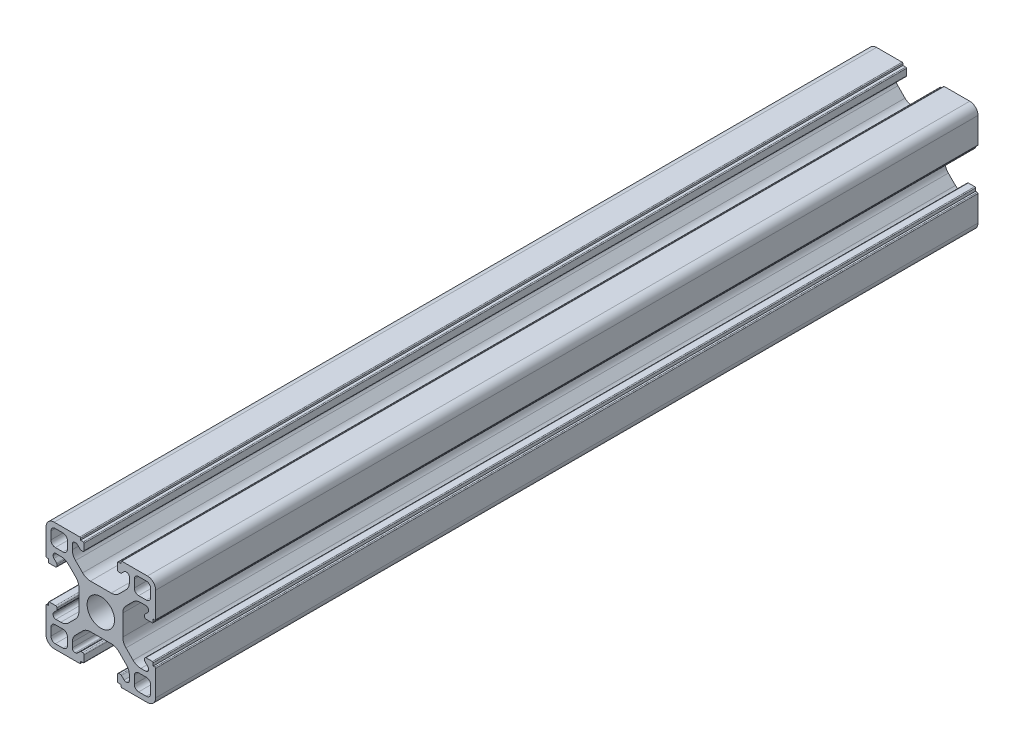
SolidWorks part; units mm, degrees
material "1060 Сплав"
ref_plane "Спереди" through (0, 0, 0) normal (0, 0, 1) x (1, 0, 0)
ref_plane "Сверху" through (0, 0, 0) normal (0, 1, 0) x (1, 0, 0)
ref_plane "Справа" through (0, 0, 0) normal (1, 0, 0) x (0, 0, -1)
sketch "Эскиз1" plane through (0, 0, 0) normal (0, 0, 1) x (1, 0, 0)
  line L0 (-22.0052, 70.3096) -> (-25.0052, 67.3096) construction
  line L1 (-31.1052, 65.2096) -> (-29.2064, 65.2096)
  line L2 (-31.1052, 61.2096) -> (-21.1052, 71.2096) construction
  line L3 (-23.5052, 68.8096) -> (-25.0052, 70.3096) construction
  line L4 (-27.7922, 65.7954) -> (-26.4909, 67.0967)
  line L5 (-24.2052, 67.3096) -> (-22.8052, 67.3096)
  line L6 (-25.0052, 68.1096) -> (-25.0052, 69.5096)
  line L7 (-22.8052, 70.3096) -> (-24.2052, 70.3096)
  line L8 (-25.9052, 69.4096) -> (-25.9052, 68.5109)
  line L9 (-27.3419, 69.2829) -> (-26.8616, 69.7632)
  line L10 (-27.9052, 70.7587) -> (-27.4052, 70.7587)
  line L11 (-27.5187, 69.2096) -> (-27.8052, 69.2096)
  line L12 (-26.508, 69.9096) -> (-26.4052, 69.9096)
  line L13 (-27.4052, 71.0596) -> (-27.4052, 70.7587)
  line L14 (-28.0552, 70.6087) -> (-28.0552, 69.4596)
  line L15 (-22.6052, 71.2096) -> (-27.2552, 71.2096)
  line L16 (-22.0052, 69.5096) -> (-22.0052, 68.1096)
  line L17 (-21.1052, 69.7096) -> (-21.1052, 65.0596)
  line L18 (-21.7061, 64.2596) -> (-22.8552, 64.2596)
  line L19 (-21.2552, 64.9096) -> (-21.5561, 64.9096)
  line L20 (-22.4052, 65.8068) -> (-22.4052, 65.9096)
  line L21 (-23.1052, 64.7961) -> (-23.1052, 64.5096)
  line L22 (-21.5561, 64.4096) -> (-21.5561, 64.9096)
  line L23 (-23.0319, 64.9729) -> (-22.5516, 65.4532)
  line L24 (-22.9052, 66.4096) -> (-23.8039, 66.4096)
  line L25 (-26.5194, 64.5226) -> (-25.2181, 65.8239)
  line L26 (-27.1052, 61.2096) -> (-27.1052, 63.1084)
  line L27 (-27.1052, 61.2096) -> (-27.1052, 59.3109)
  line L28 (-26.5194, 57.8967) -> (-25.2181, 56.5954)
  line L29 (-25.0052, 54.3096) -> (-25.0052, 52.9096)
  line L30 (-24.2052, 55.1096) -> (-22.8052, 55.1096)
  line L31 (-22.0052, 52.9096) -> (-22.0052, 54.3096)
  line L32 (-22.9052, 56.0096) -> (-23.8039, 56.0096)
  line L33 (-23.0319, 57.4464) -> (-22.5516, 56.9661)
  line L34 (-21.5561, 58.0096) -> (-21.5561, 57.5096)
  line L35 (-23.1052, 57.6232) -> (-23.1052, 57.9096)
  line L36 (-22.4052, 56.6125) -> (-22.4052, 56.5096)
  line L37 (-21.2552, 57.5096) -> (-21.5561, 57.5096)
  line L38 (-21.7061, 58.1596) -> (-22.8552, 58.1596)
  line L39 (-21.1052, 52.7096) -> (-21.1052, 57.3596)
  line L40 (-22.8052, 52.1096) -> (-24.2052, 52.1096)
  line L41 (-22.6052, 51.2096) -> (-27.2552, 51.2096)
  line L42 (-28.0552, 51.8106) -> (-28.0552, 52.9596)
  line L43 (-27.4052, 51.3596) -> (-27.4052, 51.6606)
  line L44 (-26.508, 52.5096) -> (-26.4052, 52.5096)
  line L45 (-27.5187, 53.2096) -> (-27.8052, 53.2096)
  line L46 (-27.9052, 51.6606) -> (-27.4052, 51.6606)
  line L47 (-27.3419, 53.1364) -> (-26.8616, 52.6561)
  line L48 (-25.9052, 53.0096) -> (-25.9052, 53.9084)
  line L49 (-27.7922, 56.6239) -> (-26.4909, 55.3226)
  line L50 (-31.1052, 57.2096) -> (-29.2064, 57.2096)
  line L51 (-22.0052, 52.1096) -> (-25.0052, 55.1096) construction
  line L52 (-31.1052, 61.2096) -> (-21.1052, 51.2096) construction
  line L53 (-23.5052, 53.6096) -> (-22.0052, 55.1096) construction
  line L54 (-31.1052, 57.2096) -> (-33.0039, 57.2096)
  line L55 (-34.4181, 56.6239) -> (-35.7194, 55.3226)
  line L56 (-38.0052, 55.1096) -> (-39.4052, 55.1096)
  line L57 (-37.2052, 54.3096) -> (-37.2052, 52.9096)
  line L58 (-39.4052, 52.1096) -> (-38.0052, 52.1096)
  line L59 (-36.3052, 53.0096) -> (-36.3052, 53.9084)
  line L60 (-34.8684, 53.1364) -> (-35.3487, 52.6561)
  line L61 (-34.3052, 51.6606) -> (-34.8052, 51.6606)
  line L62 (-34.6916, 53.2096) -> (-34.4052, 53.2096)
  line L63 (-35.7023, 52.5096) -> (-35.8052, 52.5096)
  line L64 (-34.8052, 51.3596) -> (-34.8052, 51.6606)
  line L65 (-34.1552, 51.8106) -> (-34.1552, 52.9596)
  line L66 (-39.6052, 51.2096) -> (-34.9552, 51.2096)
  line L67 (-40.2052, 52.9096) -> (-40.2052, 54.3096)
  line L68 (-41.1052, 52.7096) -> (-41.1052, 57.3596)
  line L69 (-40.5042, 58.1596) -> (-39.3552, 58.1596)
  line L70 (-40.9552, 57.5096) -> (-40.6542, 57.5096)
  line L71 (-39.8052, 56.6125) -> (-39.8052, 56.5096)
  line L72 (-39.1052, 57.6232) -> (-39.1052, 57.9096)
  line L73 (-40.6542, 58.0096) -> (-40.6542, 57.5096)
  line L74 (-39.1784, 57.4464) -> (-39.6587, 56.9661)
  line L75 (-39.3052, 56.0096) -> (-38.4064, 56.0096)
  line L76 (-35.6909, 57.8967) -> (-36.9922, 56.5954)
  line L77 (-35.1052, 61.2096) -> (-35.1052, 59.3109)
  line L78 (-40.2052, 52.1096) -> (-37.2052, 55.1096) construction
  line L79 (-31.1052, 61.2096) -> (-41.1052, 51.2096) construction
  line L80 (-38.7052, 53.6096) -> (-37.2052, 52.1096) construction
  line L81 (-35.1052, 61.2096) -> (-35.1052, 63.1084)
  line L82 (-35.6909, 64.5226) -> (-36.9922, 65.8239)
  line L83 (-37.2052, 68.1096) -> (-37.2052, 69.5096)
  line L84 (-38.0052, 67.3096) -> (-39.4052, 67.3096)
  line L85 (-40.2052, 69.5096) -> (-40.2052, 68.1096)
  line L86 (-39.3052, 66.4096) -> (-38.4064, 66.4096)
  line L87 (-39.1784, 64.9729) -> (-39.6587, 65.4532)
  line L88 (-40.6542, 64.4096) -> (-40.6542, 64.9096)
  line L89 (-39.1052, 64.7961) -> (-39.1052, 64.5096)
  line L90 (-39.8052, 65.8068) -> (-39.8052, 65.9096)
  line L91 (-40.9552, 64.9096) -> (-40.6542, 64.9096)
  line L92 (-40.5042, 64.2596) -> (-39.3552, 64.2596)
  line L93 (-41.1052, 69.7096) -> (-41.1052, 65.0596)
  line L94 (-39.4052, 70.3096) -> (-38.0052, 70.3096)
  line L95 (-39.6052, 71.2096) -> (-34.9552, 71.2096)
  line L96 (-34.1552, 70.6087) -> (-34.1552, 69.4596)
  line L97 (-34.8052, 71.0596) -> (-34.8052, 70.7587)
  line L98 (-35.7023, 69.9096) -> (-35.8052, 69.9096)
  line L99 (-34.6916, 69.2096) -> (-34.4052, 69.2096)
  line L100 (-34.3052, 70.7587) -> (-34.8052, 70.7587)
  line L101 (-34.8684, 69.2829) -> (-35.3487, 69.7632)
  line L102 (-36.3052, 69.4096) -> (-36.3052, 68.5109)
  line L103 (-34.4181, 65.7954) -> (-35.7194, 67.0967)
  line L104 (-31.1052, 65.2096) -> (-33.0039, 65.2096)
  line L105 (-42.8692, 61.2096) -> (-19.6008, 61.2096) construction
  line L106 (-40.2052, 70.3096) -> (-37.2052, 67.3096) construction
  line L107 (-31.1052, 49.1232) -> (-31.1052, 71.9286) construction
  line L108 (-31.1052, 61.2096) -> (-41.1052, 71.2096) construction
  line L109 (-38.7052, 68.8096) -> (-40.2052, 67.3096) construction
  arc A0 (-22.0052, 69.5096) -> (-22.8052, 70.3096) centre (-22.8052, 69.5096) ccw
  arc A1 (-24.2052, 70.3096) -> (-25.0052, 69.5096) centre (-24.2052, 69.5096) ccw
  arc A2 (-24.2052, 67.3096) -> (-25.0052, 68.1096) centre (-24.2052, 68.1096) cw
  arc A3 (-22.6052, 71.2096) -> (-21.1052, 69.7096) centre (-22.6052, 69.7096) cw
  arc A4 (-27.9052, 70.7587) -> (-28.0552, 70.6087) centre (-27.9052, 70.6087) ccw
  arc A5 (-27.2552, 71.2096) -> (-27.4052, 71.0596) centre (-27.2552, 71.0596) ccw
  arc A6 (-27.5187, 69.2096) -> (-27.3419, 69.2829) centre (-27.5187, 69.4596) ccw
  arc A7 (-27.8052, 69.2096) -> (-28.0552, 69.4596) centre (-27.8052, 69.4596) cw
  arc A8 (-26.8616, 69.7632) -> (-26.508, 69.9096) centre (-26.508, 69.4096) cw
  arc A9 (-26.4052, 69.9096) -> (-25.9052, 69.4096) centre (-26.4052, 69.4096) cw
  arc A10 (-28.6052, 61.2096) -> (-31.1052, 63.7096) centre (-31.1052, 61.2096) ccw
  arc A11 (-29.2064, 65.2096) -> (-27.7922, 65.7954) centre (-29.2064, 67.2096) ccw
  arc A12 (-25.9052, 68.5109) -> (-26.4909, 67.0967) centre (-27.9052, 68.5109) cw
  arc A13 (-22.0052, 68.1096) -> (-22.8052, 67.3096) centre (-22.8052, 68.1096) cw
  arc A14 (-22.4052, 65.9096) -> (-22.9052, 66.4096) centre (-22.9052, 65.9096) ccw
  arc A15 (-22.5516, 65.4532) -> (-22.4052, 65.8068) centre (-22.9052, 65.8068) ccw
  arc A16 (-23.1052, 64.5096) -> (-22.8552, 64.2596) centre (-22.8552, 64.5096) ccw
  arc A17 (-23.1052, 64.7961) -> (-23.0319, 64.9729) centre (-22.8552, 64.7961) cw
  arc A18 (-21.1052, 65.0596) -> (-21.2552, 64.9096) centre (-21.2552, 65.0596) cw
  arc A19 (-21.5561, 64.4096) -> (-21.7061, 64.2596) centre (-21.7061, 64.4096) cw
  arc A20 (-23.8039, 66.4096) -> (-25.2181, 65.8239) centre (-23.8039, 64.4096) ccw
  arc A21 (-27.1052, 63.1084) -> (-26.5194, 64.5226) centre (-25.1052, 63.1084) cw
  arc A22 (-22.8052, 52.1096) -> (-22.0052, 52.9096) centre (-22.8052, 52.9096) ccw
  arc A23 (-22.0052, 54.3096) -> (-22.8052, 55.1096) centre (-22.8052, 54.3096) ccw
  arc A24 (-25.0052, 54.3096) -> (-24.2052, 55.1096) centre (-24.2052, 54.3096) cw
  arc A25 (-21.1052, 52.7096) -> (-22.6052, 51.2096) centre (-22.6052, 52.7096) cw
  arc A26 (-21.5561, 58.0096) -> (-21.7061, 58.1596) centre (-21.7061, 58.0096) ccw
  arc A27 (-21.1052, 57.3596) -> (-21.2552, 57.5096) centre (-21.2552, 57.3596) ccw
  arc A28 (-23.1052, 57.6232) -> (-23.0319, 57.4464) centre (-22.8552, 57.6232) ccw
  arc A29 (-23.1052, 57.9096) -> (-22.8552, 58.1596) centre (-22.8552, 57.9096) cw
  arc A30 (-22.5516, 56.9661) -> (-22.4052, 56.6125) centre (-22.9052, 56.6125) cw
  arc A31 (-22.4052, 56.5096) -> (-22.9052, 56.0096) centre (-22.9052, 56.5096) cw
  arc A32 (-31.1052, 58.7096) -> (-28.6052, 61.2096) centre (-31.1052, 61.2096) ccw
  arc A33 (-27.1052, 59.3109) -> (-26.5194, 57.8967) centre (-25.1052, 59.3109) ccw
  arc A34 (-23.8039, 56.0096) -> (-25.2181, 56.5954) centre (-23.8039, 58.0096) cw
  arc A35 (-24.2052, 52.1096) -> (-25.0052, 52.9096) centre (-24.2052, 52.9096) cw
  arc A36 (-26.4052, 52.5096) -> (-25.9052, 53.0096) centre (-26.4052, 53.0096) ccw
  arc A37 (-26.8616, 52.6561) -> (-26.508, 52.5096) centre (-26.508, 53.0096) ccw
  arc A38 (-27.8052, 53.2096) -> (-28.0552, 52.9596) centre (-27.8052, 52.9596) ccw
  arc A39 (-27.5187, 53.2096) -> (-27.3419, 53.1364) centre (-27.5187, 52.9596) cw
  arc A40 (-27.2552, 51.2096) -> (-27.4052, 51.3596) centre (-27.2552, 51.3596) cw
  arc A41 (-27.9052, 51.6606) -> (-28.0552, 51.8106) centre (-27.9052, 51.8106) cw
  arc A42 (-25.9052, 53.9084) -> (-26.4909, 55.3226) centre (-27.9052, 53.9084) ccw
  arc A43 (-29.2064, 57.2096) -> (-27.7922, 56.6239) centre (-29.2064, 55.2096) cw
  arc A44 (-40.2052, 52.9096) -> (-39.4052, 52.1096) centre (-39.4052, 52.9096) ccw
  arc A45 (-38.0052, 52.1096) -> (-37.2052, 52.9096) centre (-38.0052, 52.9096) ccw
  arc A46 (-38.0052, 55.1096) -> (-37.2052, 54.3096) centre (-38.0052, 54.3096) cw
  arc A47 (-39.6052, 51.2096) -> (-41.1052, 52.7096) centre (-39.6052, 52.7096) cw
  arc A48 (-34.3052, 51.6606) -> (-34.1552, 51.8106) centre (-34.3052, 51.8106) ccw
  arc A49 (-34.9552, 51.2096) -> (-34.8052, 51.3596) centre (-34.9552, 51.3596) ccw
  arc A50 (-34.6916, 53.2096) -> (-34.8684, 53.1364) centre (-34.6916, 52.9596) ccw
  arc A51 (-34.4052, 53.2096) -> (-34.1552, 52.9596) centre (-34.4052, 52.9596) cw
  arc A52 (-35.3487, 52.6561) -> (-35.7023, 52.5096) centre (-35.7023, 53.0096) cw
  arc A53 (-35.8052, 52.5096) -> (-36.3052, 53.0096) centre (-35.8052, 53.0096) cw
  arc A54 (-33.6052, 61.2096) -> (-31.1052, 58.7096) centre (-31.1052, 61.2096) ccw
  arc A55 (-33.0039, 57.2096) -> (-34.4181, 56.6239) centre (-33.0039, 55.2096) ccw
  arc A56 (-36.3052, 53.9084) -> (-35.7194, 55.3226) centre (-34.3052, 53.9084) cw
  arc A57 (-40.2052, 54.3096) -> (-39.4052, 55.1096) centre (-39.4052, 54.3096) cw
  arc A58 (-39.8052, 56.5096) -> (-39.3052, 56.0096) centre (-39.3052, 56.5096) ccw
  arc A59 (-39.6587, 56.9661) -> (-39.8052, 56.6125) centre (-39.3052, 56.6125) ccw
  arc A60 (-39.1052, 57.9096) -> (-39.3552, 58.1596) centre (-39.3552, 57.9096) ccw
  arc A61 (-39.1052, 57.6232) -> (-39.1784, 57.4464) centre (-39.3552, 57.6232) cw
  arc A62 (-41.1052, 57.3596) -> (-40.9552, 57.5096) centre (-40.9552, 57.3596) cw
  arc A63 (-40.6542, 58.0096) -> (-40.5042, 58.1596) centre (-40.5042, 58.0096) cw
  arc A64 (-38.4064, 56.0096) -> (-36.9922, 56.5954) centre (-38.4064, 58.0096) ccw
  arc A65 (-35.1052, 59.3109) -> (-35.6909, 57.8967) centre (-37.1052, 59.3109) cw
  arc A66 (-39.4052, 70.3096) -> (-40.2052, 69.5096) centre (-39.4052, 69.5096) ccw
  arc A67 (-40.2052, 68.1096) -> (-39.4052, 67.3096) centre (-39.4052, 68.1096) ccw
  arc A68 (-37.2052, 68.1096) -> (-38.0052, 67.3096) centre (-38.0052, 68.1096) cw
  arc A69 (-41.1052, 69.7096) -> (-39.6052, 71.2096) centre (-39.6052, 69.7096) cw
  arc A70 (-40.6542, 64.4096) -> (-40.5042, 64.2596) centre (-40.5042, 64.4096) ccw
  arc A71 (-41.1052, 65.0596) -> (-40.9552, 64.9096) centre (-40.9552, 65.0596) ccw
  arc A72 (-39.1052, 64.7961) -> (-39.1784, 64.9729) centre (-39.3552, 64.7961) ccw
  arc A73 (-39.1052, 64.5096) -> (-39.3552, 64.2596) centre (-39.3552, 64.5096) cw
  arc A74 (-39.6587, 65.4532) -> (-39.8052, 65.8068) centre (-39.3052, 65.8068) cw
  arc A75 (-39.8052, 65.9096) -> (-39.3052, 66.4096) centre (-39.3052, 65.9096) cw
  arc A76 (-31.1052, 63.7096) -> (-33.6052, 61.2096) centre (-31.1052, 61.2096) ccw
  arc A77 (-35.1052, 63.1084) -> (-35.6909, 64.5226) centre (-37.1052, 63.1084) ccw
  arc A78 (-38.4064, 66.4096) -> (-36.9922, 65.8239) centre (-38.4064, 64.4096) cw
  arc A79 (-38.0052, 70.3096) -> (-37.2052, 69.5096) centre (-38.0052, 69.5096) cw
  arc A80 (-35.8052, 69.9096) -> (-36.3052, 69.4096) centre (-35.8052, 69.4096) ccw
  arc A81 (-35.3487, 69.7632) -> (-35.7023, 69.9096) centre (-35.7023, 69.4096) ccw
  arc A82 (-34.4052, 69.2096) -> (-34.1552, 69.4596) centre (-34.4052, 69.4596) ccw
  arc A83 (-34.6916, 69.2096) -> (-34.8684, 69.2829) centre (-34.6916, 69.4596) cw
  arc A84 (-34.9552, 71.2096) -> (-34.8052, 71.0596) centre (-34.9552, 71.0596) cw
  arc A85 (-34.3052, 70.7587) -> (-34.1552, 70.6087) centre (-34.3052, 70.6087) cw
  arc A86 (-36.3052, 68.5109) -> (-35.7194, 67.0967) centre (-34.3052, 68.5109) ccw
  arc A87 (-33.0039, 65.2096) -> (-34.4181, 65.7954) centre (-33.0039, 67.2096) cw
  point P0 (-31.1052, 61.2096)
  point P9 (-31.1052, 61.2096)
  point P40 (-22.4052, 64.9096)
  point P93 (-27.4052, 52.5096)
  point P144 (-27.4052, 69.9096)
  point P152 (-22.4052, 57.5096)
  point P153 (-31.1052, 57.2854)
  point P154 (-31.1052, 61.2096)
  point P189 (-39.8052, 57.5096)
  point P228 (-34.8052, 52.5096)
  point P229 (-35.0294, 61.2096)
  point P230 (-31.1052, 61.2096)
  point P268 (-34.8052, 69.9096)
  point P273 (-27.1809, 61.2096)
  point P306 (-39.8052, 64.9096)
  point P307 (-31.1052, 65.1339)
  point P309 (-31.1052, 61.2096)
  dimension "D3" = 5
  dimension "D6" = 2
  dimension "D1" = 2
  dimension "D2" = 6
  dimension "D4" = 4
  dimension "D5" = 0.9
extrude "Бобышка-Вытянуть1" add sketch "Эскиз1" along normal blind 150
